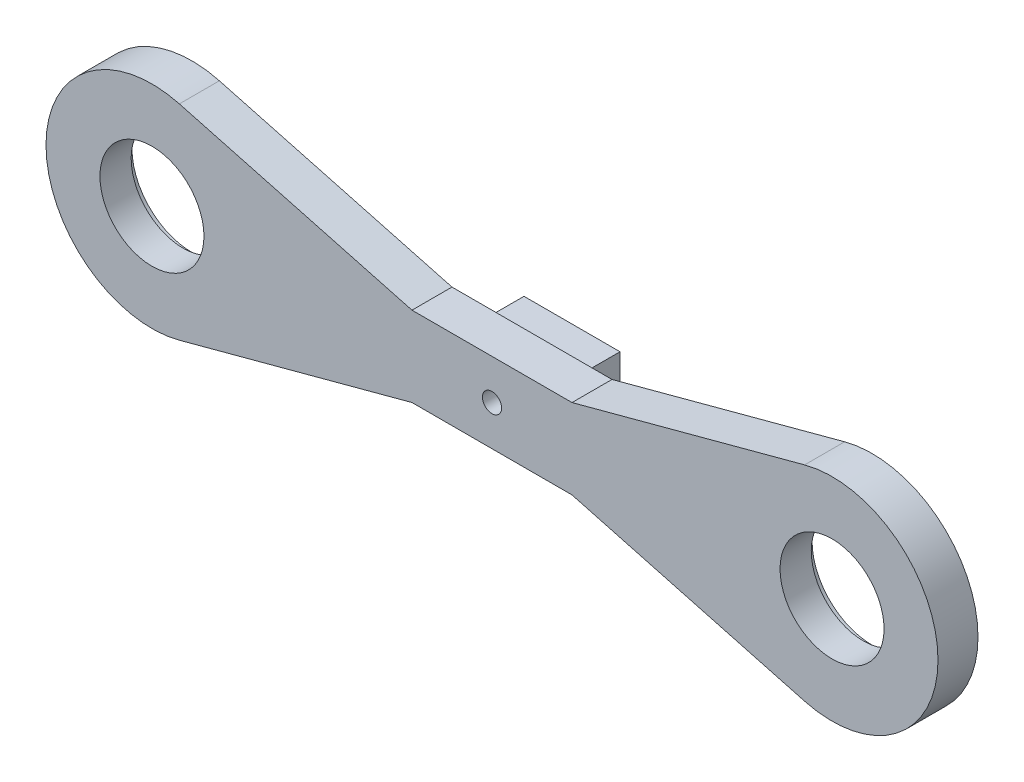
SolidWorks part; units mm, degrees
ref_plane "前视基准面" through (0, 0, 0) normal (0, 0, 1) x (1, 0, 0)
ref_plane "上视基准面" through (0, 0, 0) normal (0, 1, 0) x (1, 0, 0)
ref_plane "右视基准面" through (0, 0, 0) normal (1, 0, 0) x (0, 0, -1)
sketch "草图1" plane through (0, 0, 0) normal (0, 0, 1) x (1, 0, 0)
  line L0 (1.8019, 0) -> (93.6019, 0) construction
  line L1 (0, -0.6006) -> (0, -78.6006) construction
  line L2 (-10, 5) -> (10, 5)
  line L3 (10, 5) -> (39.0729, 12.7901)
  line L4 (-10, 5) -> (-39.0729, 12.7901)
  line L5 (10, -5) -> (39.0729, -12.7901)
  line L6 (-10, -5) -> (10, -5)
  line L7 (-10, -5) -> (-39.0729, -12.7901)
  arc A0 (-39.0729, 12.7901) -> (-39.0729, -12.7901) centre (-42.5, 0) ccw
  arc A1 (39.0729, 12.7901) -> (39.0729, -12.7901) centre (42.5, 0) cw
  circle A2 centre (-42.5, 0) radius 6.5
  circle A3 centre (42.5, 0) radius 6.5
  point P16 (0, 5)
  dimension "D6" = 13
  dimension "D7" = 13
  dimension "D1" = 10
  dimension "D2" = 165
  dimension "D3" = 165
  dimension "D4" = 20
  dimension "D5" = 85
extrude "凸台-拉伸1" add sketch "草图1" along normal blind 5
sketch "草图2" plane through (0, 0, 0) normal (0, 0, -1) x (-1, 0, 0)
  line L1 (-5, 2.5) -> (5, 2.5)
  line L2 (-5, 2.5) -> (-5, -2.5)
  line L3 (-5, -2.5) -> (5, -2.5)
  line L4 (5, 2.5) -> (5, -2.5)
  line L6 (39.0729, 12.7901) -> (10, 5)
  line L7 (10, 5) -> (-10, 5)
  line L8 (-10, 5) -> (-39.0729, 12.7901)
  line L9 (-39.0729, -12.7901) -> (-10, -5)
  line L10 (-10, -5) -> (10, -5)
  line L11 (10, -5) -> (39.0729, -12.7901)
  line L12 (39.0729, 12.7901) -> (10, 5)
  line L13 (10, 5) -> (-10, 5)
  line L14 (-10, 5) -> (-39.0729, 12.7901)
  line L15 (-39.0729, -12.7901) -> (-10, -5)
  line L16 (-10, -5) -> (10, -5)
  line L17 (10, -5) -> (39.0729, -12.7901)
  arc A2 (-39.0729, 12.7901) -> (-39.0729, -12.7901) centre (-42.5, 0) ccw
  arc A3 (39.0729, -12.7901) -> (39.0729, 12.7901) centre (42.5, 0) ccw
  arc A4 (-39.0729, 12.7901) -> (-39.0729, -12.7901) centre (-42.5, 0) ccw
  arc A5 (39.0729, -12.7901) -> (39.0729, 12.7901) centre (42.5, 0) ccw
  dimension "D2" = 10
  dimension "D3" = 5
  dimension "D4" = 2.5
  dimension "D5" = 5
  dimension "D1" = 0
extrude "拉伸-薄壁1" add sketch "草图2" along normal blind 5 thin contours L4 L1 L2 L3
sketch "草图3" plane through (0, 0, 0) normal (0, 0, -1) x (-1, 0, 0)
  line L4 (5, -2.5) -> (5, 2.5)
  line L5 (5, 2.5) -> (-5, 2.5)
  line L6 (-5, 2.5) -> (-5, -2.5)
  line L7 (-5, -2.5) -> (5, -2.5)
  line L8 (5, -2.5) -> (5, 2.5)
  line L9 (5, 2.5) -> (-5, 2.5)
  line L10 (-5, 2.5) -> (-5, -2.5)
  line L11 (-5, -2.5) -> (5, -2.5)
  circle A0 centre (0, 0) radius 1.2
  dimension "D2" = 2.4
  dimension "D1" = 0
extrude "切除-拉伸1" cut sketch "草图3" against normal blind 5 contours A0
sketch "草图4" plane through (0, 0, 0) normal (0, 0, -1) x (-1, 0, 0)
  circle A0 centre (-42.5, 0) radius 7.5
  circle A1 centre (42.5, 0) radius 7.5
extrude "切除-拉伸2" cut sketch "草图4" against normal blind 1.1 contours A1 | A0
